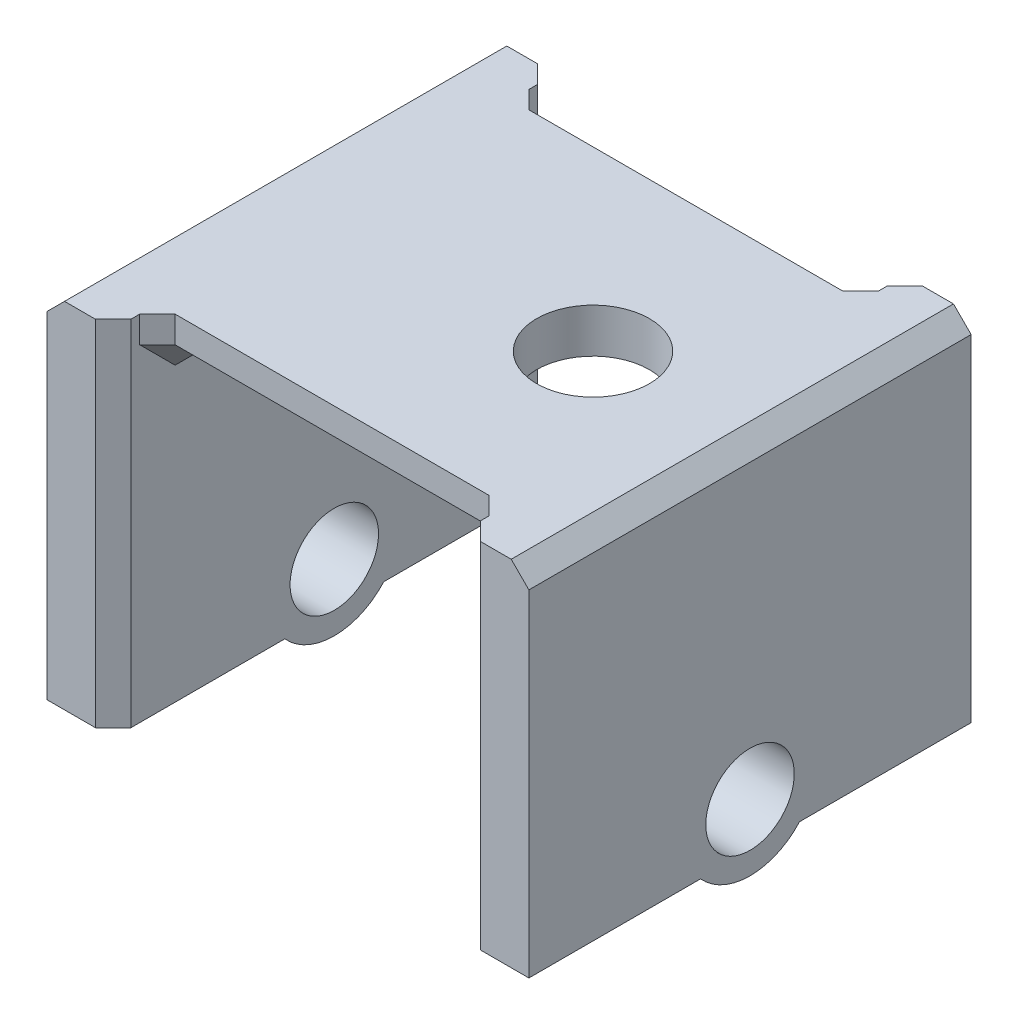
SolidWorks part; units mm, degrees
ref_plane "Front Plane" through (0, 0, 0) normal (0, 0, 1) x (1, 0, 0)
ref_plane "Top Plane" through (0, 0, 0) normal (0, 1, 0) x (1, 0, 0)
ref_plane "Right Plane" through (0, 0, 0) normal (1, 0, 0) x (0, 0, -1)
sketch "Sketch1" plane through (0, 0, 0) normal (0, 0, 1) x (1, 0, 0)
  line L0 (-27.25, 0) -> (-19.75, 0)
  line L1 (-19.75, 0) -> (-19.75, 35)
  line L2 (-27.25, 40) -> (27.25, 40)
  line L3 (-27.25, 0) -> (-27.25, 40)
  line L4 (-19.75, 35) -> (19.75, 35)
  line L5 (0, 0) -> (0, 27.4247) construction
  line L6 (19.75, 0) -> (19.75, 35)
  line L7 (27.25, 0) -> (19.75, 0)
  line L8 (27.25, 0) -> (27.25, 40)
  point P10 (0, 35)
  point P14 (0, 40)
  dimension "D1" = 27.25
  dimension "D2" = 7.5
  dimension "D3" = 0
  dimension "D4" = 40
  dimension "D5" = 5
extrude "Boss-Extrude1" add sketch "Sketch1" along normal blind 50
sketch "Sketch3" plane through (0, 35, 0) normal (0, -1, 0) x (-1, 0, 0)
  line L0 (19.75, 0) -> (19.75, -5)
  line L1 (19.75, -50) -> (19.75, 0) construction
  line L2 (19.75, -5) -> (-19.75, -5)
  line L3 (-19.75, -50) -> (-19.75, 0) construction
  line L4 (-19.75, -5) -> (-19.75, 0)
  line L5 (19.75, 0) -> (-19.75, 0) construction
  line L6 (27.25, -25) -> (-31.2352, -25) construction
  line L7 (27.25, -50) -> (27.25, 0) construction
  line L8 (-19.75, -45) -> (-19.75, -50)
  line L9 (19.75, -50) -> (19.75, -45)
  line L10 (19.75, -45) -> (-19.75, -45)
  line L11 (-19.75, 0) -> (19.75, 0)
  line L12 (-19.75, -50) -> (19.75, -50)
  dimension "D1" = 5
extrude "Cut-Extrude1" cut sketch "Sketch3" against normal through all both and the other way through all
chamfer "Chamfer1" distance 2 angle 45 14 edges at (19.75, 20, 50) (19.75, 20, 0) (-19.75, 20, 0) (-19.75, 20, 50) (0, 35, 5) (19.75, 37.5, 5) (19.75, 37.5, 45) (19.75, 35, 25) (0, 35, 45) (-19.75, 37.5, 5) (-19.75, 37.5, 45) (-19.75, 35, 25) (27.25, 40, 25) (-27.25, 40, 25)
sketch "Sketch4" plane through (-27.25, 0, 0) normal (-1, 0, 0) x (0, 0, 1)
  line L0 (50, 0) -> (0, 0) construction
  line L1 (30.5902, 0) -> (19.4098, 0)
  line L2 (0, 38) -> (0, 0) construction
  arc A0 (19.4098, 0) -> (30.5902, 0) centre (25, 5) ccw
  dimension "D1" = 15
  dimension "D2" = 5
  dimension "D3" = 25
extrude "Boss-Extrude2" add sketch "Sketch4" against normal blind 7.5
sketch "Sketch5" plane through (-27.25, 0, 0) normal (-1, 0, 0) x (0, 0, 1)
  circle A0 centre (25, 5) radius 5
  dimension "D1" = 10
extrude "Cut-Extrude4" cut sketch "Sketch5" against normal up to next and the other way through all contours A0
mirror "Mirror1" about plane through (0, 0, 0) normal (1, 0, 0) of "Cut-Extrude4", "Boss-Extrude2"
sketch "Sketch6" plane through (0, 35, 0) normal (0, -1, 0) x (1, 0, 0)
  line L1 (19.75, 43) -> (19.75, 7) construction
  circle A0 centre (9.5, 25) radius 6.375
  dimension "D1" = 10.25
  dimension "D2" = 12.75
extrude "Cut-Extrude5" cut sketch "Sketch6" against normal through all
